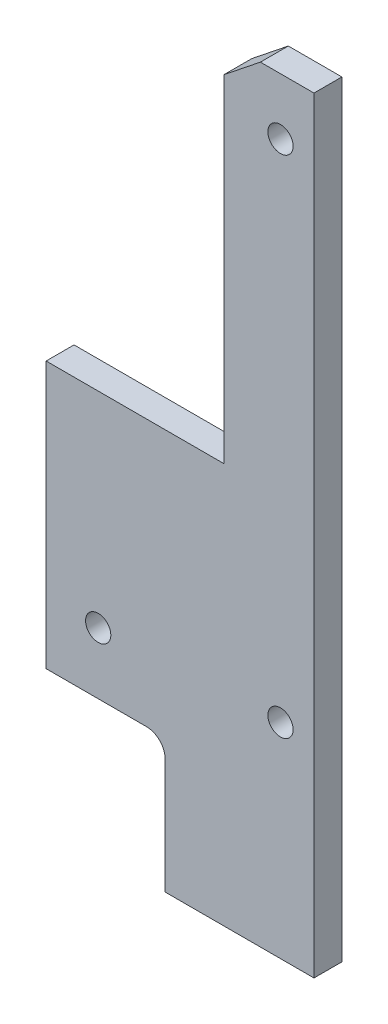
SolidWorks part; units mm, degrees
ref_plane "Front Plane" through (0, 0, 0) normal (0, 0, 1) x (1, 0, 0)
ref_plane "Top Plane" through (0, 0, 0) normal (0, 1, 0) x (1, 0, 0)
ref_plane "Right Plane" through (0, 0, 0) normal (1, 0, 0) x (0, 0, -1)
sketch "Sketch1" plane through (0, 0, 0) normal (0, 0, 1) x (1, 0, 0)
  line L0 (-25.4, 0) -> (0, 0) construction
  line L1 (-25.4, 19.685) -> (-25.4, 0) construction
  line L2 (-45.72, 22.86) -> (-28.575, 22.86) construction
  line L3 (-15.3921, 125.8202) -> (-15.3921, 68.3432)
  line L4 (-15.3921, 68.3432) -> (-45.72, 68.3432)
  line L5 (-9.144, 130.81) -> (-45.72, 101.6) construction
  line L6 (0, 130.81) -> (0, 0)
  line L7 (-15.3921, 125.8202) -> (-9.144, 130.81)
  line L8 (-9.144, 130.81) -> (0, 130.81)
  line L19 (-25.4, 0) -> (0, 0)
  line L20 (-25.4, 19.685) -> (-25.4, 0)
  line L21 (-45.72, 22.86) -> (-28.575, 22.86)
  line L22 (-45.72, 68.3432) -> (-45.72, 22.86)
  arc A0 (-25.4, 19.685) -> (-28.575, 22.86) centre (-28.575, 19.685) ccw construction
  arc A1 (-25.4, 19.685) -> (-28.575, 22.86) centre (-28.575, 19.685) ccw
extrude "Boss-Extrude1" add sketch "Sketch1" along normal blind 4.7625
sketch "Sketch3" plane through (0, 0, 0) normal (0, 0, -1) x (-1, 0, 0)
  circle A0 centre (5.715, 121.158) radius 2.1527
  circle A1 centre (5.715, 34.925) radius 2.1526
  circle A2 centre (36.83, 33.3375) radius 2.1527
  dimension "D1" = 4.3053
extrude "Cut-Extrude1" cut sketch "Sketch3" against normal through all
